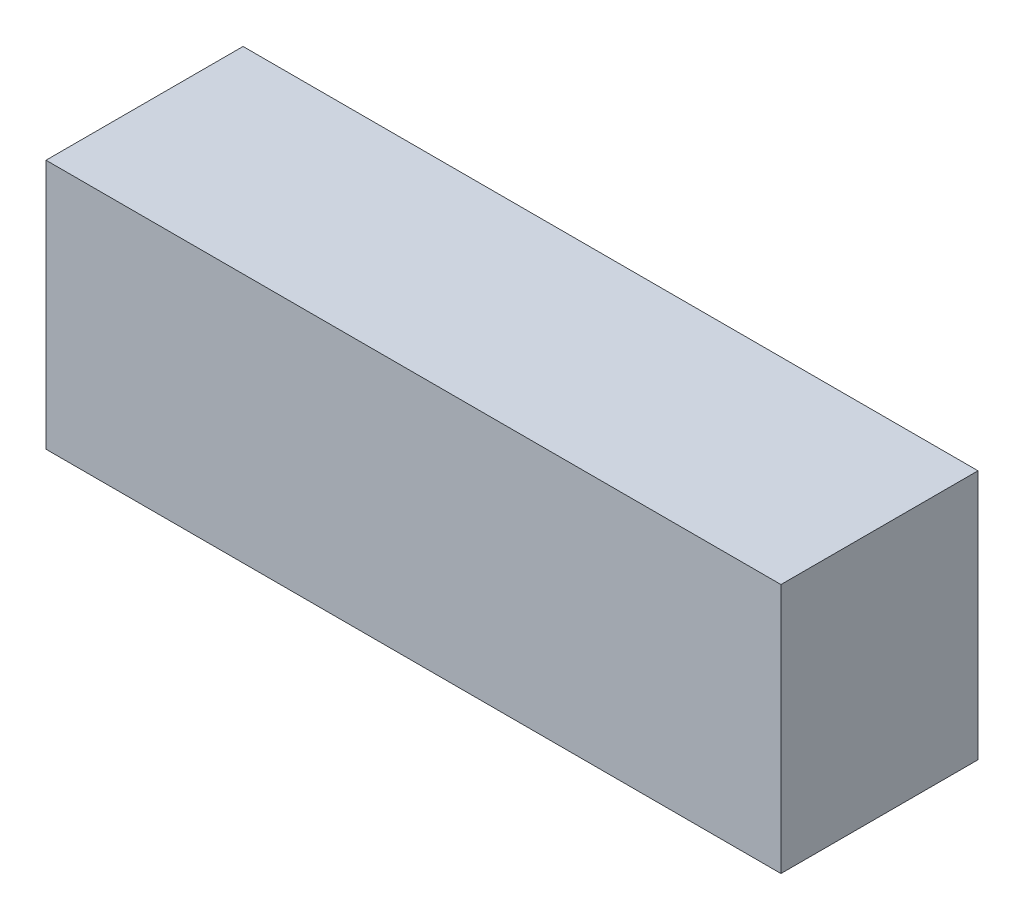
SolidWorks part; units mm, degrees
ref_plane "Front Plane" through (0, 0, 0) normal (0, 0, 1) x (1, 0, 0)
ref_plane "Top Plane" through (0, 0, 0) normal (0, 1, 0) x (1, 0, 0)
ref_plane "Right Plane" through (0, 0, 0) normal (1, 0, 0) x (0, 0, -1)
sketch "Sketch1" plane through (0, 0, 0) normal (0, 0, 1) x (1, 0, 0)
  line L1 (0, 0) -> (138, 0)
  line L2 (0, 0) -> (0, 47)
  line L3 (0, 47) -> (138, 47)
  line L4 (138, 0) -> (138, 47)
  dimension "D1" = 47
  dimension "D2" = 138
extrude "Boss-Extrude1" add sketch "Sketch1" along normal blind 37
